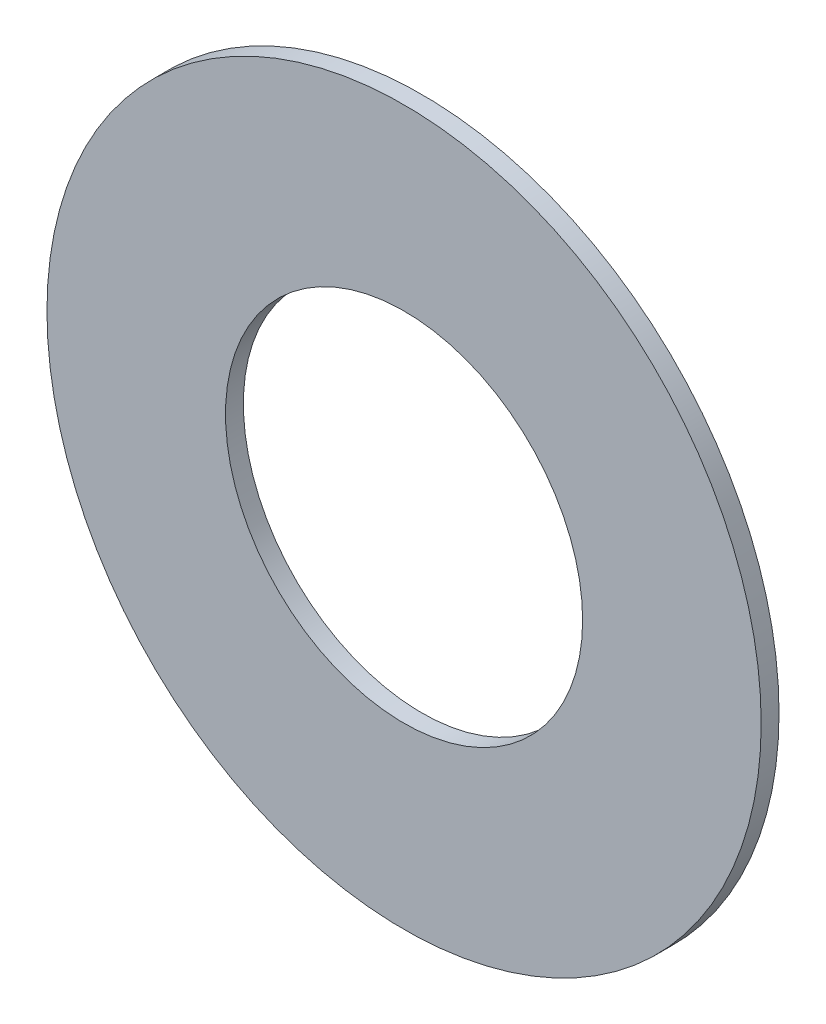
SolidWorks part; units mm, degrees
material "Alloy Steel"
ref_plane "Front Plane" through (0, 0, 0) normal (0, 0, 1) x (1, 0, 0)
ref_plane "Top Plane" through (0, 0, 0) normal (0, 1, 0) x (1, 0, 0)
ref_plane "Right Plane" through (0, 0, 0) normal (1, 0, 0) x (0, 0, -1)
sketch "Sketch1" plane through (0, 0, 0) normal (0, 0, 1) x (1, 0, 0)
  circle A0 centre (0, 0) radius 10
  circle A1 centre (0, 0) radius 5
  dimension "D1" = 20
  dimension "D2" = 10
extrude "Boss-Extrude1" add sketch "Sketch1" along normal blind 0.5
